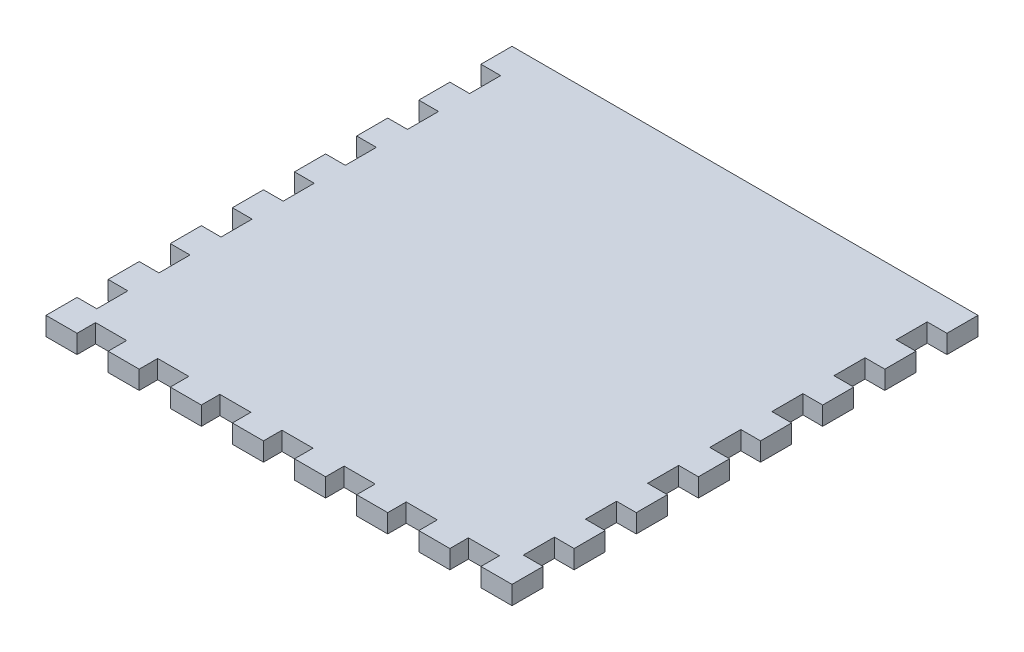
SolidWorks part; units mm, degrees
material "Acrylic (Medium-high impact)"
ref_plane "Front Plane" through (0, 0, 0) normal (0, 0, 1) x (1, 0, 0)
ref_plane "Top Plane" through (0, 0, 0) normal (0, 1, 0) x (1, 0, 0)
ref_plane "Right Plane" through (0, 0, 0) normal (1, 0, 0) x (0, 0, -1)
sketch "Sketch1" plane through (0, 0, 0) normal (0, 1, 0) x (1, 0, 0)
  line L1 (-40, -40) -> (40, -40)
  line L2 (-40, -40) -> (-40, 40)
  line L3 (-40, 40) -> (40, 40)
  line L4 (40, -40) -> (40, 40)
  line L5 (-40, -40) -> (40, 40) construction
  line L6 (-40, 40) -> (40, -40) construction
  point P0 (0, 0)
  dimension "D1" = 80
  dimension "D2" = 80
extrude "Boss-Extrude1" add sketch "Sketch1" along normal blind 3.175
sketch "Sketch3" plane through (0, 3.175, 0) normal (0, 1, 0) x (1, 0, 0)
  line L0 (0, 0) -> (50000, 0) construction
  line L1 (-40, -40) -> (-34.6667, -40)
  line L2 (34.6667, 40) -> (40, 40)
  line L3 (-34.6667, -40) -> (-34.6667, -36.825)
  line L4 (-34.6667, -36.825) -> (-29.3333, -36.825)
  line L5 (-29.3333, -36.825) -> (-29.3333, -40)
  line L6 (-29.3333, -40) -> (-24, -40)
  line L7 (-24, -40) -> (-24, -36.825)
  line L8 (-24, -36.825) -> (-18.6667, -36.825)
  line L9 (-18.6667, -36.825) -> (-18.6667, -40)
  line L10 (-18.6667, -40) -> (-13.3333, -40)
  line L11 (-13.3333, -40) -> (-13.3333, -36.825)
  line L12 (-13.3333, -36.825) -> (-8, -36.825)
  line L13 (-8, -36.825) -> (-8, -40)
  line L14 (-8, -40) -> (-2.6667, -40)
  line L15 (-2.6667, -40) -> (-2.6667, -36.825)
  line L16 (-2.6667, -36.825) -> (2.6667, -36.825)
  line L17 (2.6667, -36.825) -> (2.6667, -40)
  line L18 (2.6667, -40) -> (8, -40)
  line L19 (8, -40) -> (8, -36.825)
  line L20 (8, -36.825) -> (13.3333, -36.825)
  line L21 (13.3333, -36.825) -> (13.3333, -40)
  line L22 (13.3333, -40) -> (18.6667, -40)
  line L23 (18.6667, -40) -> (18.6667, -36.825)
  line L24 (18.6667, -36.825) -> (24, -36.825)
  line L25 (24, -36.825) -> (24, -40)
  line L26 (24, -40) -> (29.3333, -40)
  line L27 (29.3333, -40) -> (29.3333, -36.825)
  line L28 (29.3333, -36.825) -> (34.6667, -36.825)
  line L29 (34.6667, -36.825) -> (34.6667, -40)
  line L30 (34.6667, -40) -> (40, -40)
  line L31 (34.6667, 36.825) -> (34.6667, 40)
  line L32 (29.3333, 36.825) -> (34.6667, 36.825)
  line L33 (29.3333, 40) -> (29.3333, 36.825)
  line L34 (24, 40) -> (29.3333, 40)
  line L35 (24, 36.825) -> (24, 40)
  line L36 (18.6667, 36.825) -> (24, 36.825)
  line L37 (18.6667, 40) -> (18.6667, 36.825)
  line L38 (13.3333, 40) -> (18.6667, 40)
  line L39 (13.3333, 36.825) -> (13.3333, 40)
  line L40 (8, 36.825) -> (13.3333, 36.825)
  line L41 (8, 40) -> (8, 36.825)
  line L42 (2.6667, 40) -> (8, 40)
  line L43 (2.6667, 36.825) -> (2.6667, 40)
  line L44 (-2.6667, 36.825) -> (2.6667, 36.825)
  line L45 (-2.6667, 40) -> (-2.6667, 36.825)
  line L46 (-8, 40) -> (-2.6667, 40)
  line L47 (-8, 36.825) -> (-8, 40)
  line L48 (-13.3333, 36.825) -> (-8, 36.825)
  line L49 (-13.3333, 40) -> (-13.3333, 36.825)
  line L50 (-18.6667, 40) -> (-13.3333, 40)
  line L51 (-18.6667, 36.825) -> (-18.6667, 40)
  line L52 (-24, 36.825) -> (-18.6667, 36.825)
  line L53 (-24, 40) -> (-24, 36.825)
  line L54 (-29.3333, 40) -> (-24, 40)
  line L55 (-29.3333, 36.825) -> (-29.3333, 40)
  line L56 (-34.6667, 36.825) -> (-29.3333, 36.825)
  line L57 (-34.6667, 40) -> (-34.6667, 36.825)
  line L58 (-40, 40) -> (-34.6667, 40)
  line L59 (0, 0) -> (0, 50000) construction
  line L60 (40, 40) -> (40, 34.6667)
  line L61 (40, -40) -> (40, 40) construction
  line L62 (40, 34.6667) -> (36.6133, 34.6667)
  line L63 (36.6133, 34.6667) -> (36.6133, 29.3333)
  line L64 (36.6133, 29.3333) -> (40, 29.3333)
  line L65 (40, 29.3333) -> (40, 24)
  line L66 (40, 24) -> (36.6133, 24)
  line L67 (36.6133, 24) -> (36.6133, 18.6667)
  line L68 (36.6133, 18.6667) -> (40, 18.6667)
  line L69 (40, 18.6667) -> (40, 13.3333)
  line L70 (40, 13.3333) -> (36.6133, 13.3333)
  line L71 (36.6133, 13.3333) -> (36.6133, 8)
  line L72 (36.6133, 8) -> (40, 8)
  line L73 (40, 8) -> (40, 2.6667)
  line L74 (40, 2.6667) -> (36.6133, 2.6667)
  line L75 (36.6133, 2.6667) -> (36.6133, -2.6667)
  line L76 (36.6133, -2.6667) -> (40, -2.6667)
  line L77 (40, -2.6667) -> (40, -8)
  line L78 (40, -8) -> (36.6133, -8)
  line L79 (36.6133, -8) -> (36.6133, -13.3333)
  line L80 (36.6133, -13.3333) -> (40, -13.3333)
  line L81 (40, -13.3333) -> (40, -18.6667)
  line L82 (40, -18.6667) -> (36.6133, -18.6667)
  line L83 (36.6133, -18.6667) -> (36.6133, -24)
  line L84 (36.6133, -24) -> (40, -24)
  line L85 (40, -24) -> (40, -29.3333)
  line L86 (40, -29.3333) -> (36.6133, -29.3333)
  line L87 (36.6133, -29.3333) -> (36.6133, -34.6667)
  line L88 (36.6133, -34.6667) -> (40, -34.6667)
  line L89 (40, -34.6667) -> (40, -40)
  line L90 (0, 0) -> (-50000, 0) construction
  line L91 (-40, -34.6667) -> (-40, -40)
  line L92 (-36.6133, -34.6667) -> (-40, -34.6667)
  line L93 (-40, -29.3333) -> (-36.6133, -29.3333)
  line L94 (-40, -24) -> (-40, -29.3333)
  line L95 (-36.6133, -24) -> (-40, -24)
  line L96 (-40, -18.6667) -> (-36.6133, -18.6667)
  line L97 (-40, -13.3333) -> (-40, -18.6667)
  line L98 (-36.6133, -13.3333) -> (-40, -13.3333)
  line L99 (-40, -8) -> (-36.6133, -8)
  line L100 (-40, -2.6667) -> (-40, -8)
  line L101 (-36.6133, -2.6667) -> (-40, -2.6667)
  line L102 (-40, 2.6667) -> (-36.6133, 2.6667)
  line L103 (-40, 8) -> (-40, 2.6667)
  line L104 (-36.6133, 8) -> (-40, 8)
  line L105 (-40, 13.3333) -> (-36.6133, 13.3333)
  line L106 (-40, 18.6667) -> (-40, 13.3333)
  line L107 (-36.6133, 18.6667) -> (-40, 18.6667)
  line L108 (-40, 24) -> (-36.6133, 24)
  line L109 (-40, 29.3333) -> (-40, 24)
  line L110 (-36.6133, 29.3333) -> (-40, 29.3333)
  line L111 (-40, 34.6667) -> (-36.6133, 34.6667)
  line L112 (-40, 40) -> (-40, 34.6667)
  line L114 (-36.6133, -29.3333) -> (-36.6133, -34.6667)
  line L115 (-36.6133, -18.6667) -> (-36.6133, -24)
  line L116 (-36.6133, -8) -> (-36.6133, -13.3333)
  line L117 (-36.6133, 2.6667) -> (-36.6133, -2.6667)
  line L118 (-36.6133, 13.3333) -> (-36.6133, 8)
  line L119 (-36.6133, 24) -> (-36.6133, 18.6667)
  line L120 (-36.6133, 34.6667) -> (-36.6133, 29.3333)
  dimension "D1" = 5.3333
  dimension "D2" = 7
  dimension "D3" = 5.3333
extrude "Cut-Extrude1" cut sketch "Sketch3" against normal through all flip side to cut
sketch "Sketch8" plane through (0, 3.175, 0) normal (0, 1, 0) x (1, 0, 0)
  line L1 (-40, 40) -> (40, 40)
  line L2 (-40, 40) -> (-40, 34.6667)
  line L3 (-40, 34.6667) -> (40, 34.6667)
  line L4 (40, 40) -> (40, 34.6667)
extrude "Boss-Extrude2" add sketch "Sketch8" against normal up to surface (3.175 mm away) up to face at (0, 0, 0)
